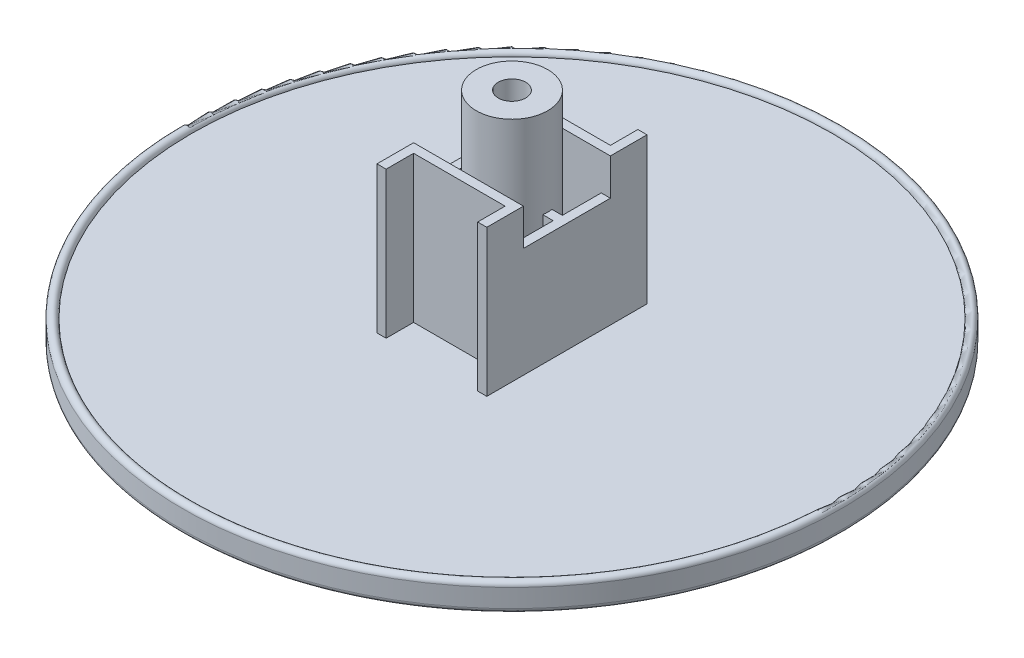
SolidWorks part; units mm, degrees
ref_plane "前视基准面" through (0, 0, 0) normal (0, 0, 1) x (1, 0, 0)
ref_plane "上视基准面" through (0, 0, 0) normal (0, 1, 0) x (1, 0, 0)
ref_plane "右视基准面" through (0, 0, 0) normal (1, 0, 0) x (0, 0, -1)
sketch "草图3" plane through (0, 0, 0) normal (0, 0, 1) x (1, 0, 0)
  line L5 (0, 0) -> (35, 0)
  line L6 (0, 0) -> (0, 2)
  line L11 (0, 2) -> (35, 2)
  line L12 (35, 0) -> (35, 2)
  line L17 (0, 0) -> (35, 2) construction
  line L18 (0, 2) -> (35, 0) construction
  line L19 (35, 0) -> (36, 0)
  line L20 (35, 0) -> (35, 2)
  line L21 (35, 2) -> (36, 2)
  line L22 (36, 0) -> (36, 2)
  line L23 (35, 0) -> (36, 2) construction
  line L24 (35, 2) -> (36, 0) construction
  line L25 (0, 2) -> (3.9, 2)
  line L26 (0, 2) -> (0, 23.6)
  line L27 (0, 23.6) -> (3.9, 23.6)
  line L28 (3.9, 2) -> (3.9, 23.6)
  line L29 (0, 2) -> (3.9, 23.6) construction
  line L30 (0, 23.6) -> (3.9, 2) construction
  line L31 (0, 2) -> (1.5, 2)
  line L32 (0, 2) -> (0, 23.6)
  line L33 (0, 23.6) -> (1.5, 23.6)
  line L34 (1.5, 2) -> (1.5, 23.6)
  line L35 (0, 2) -> (1.5, 23.6) construction
  line L36 (0, 23.6) -> (1.5, 2) construction
  circle A0 centre (35.5, 2) radius 0.5
  circle A1 centre (35.5, 0) radius 0.5
  point P5 (17.5, 1)
  point P9 (35.5, 1)
  point P14 (1.95, 12.8)
  point P19 (0.75, 12.8)
  dimension "D5" = 21.6
  dimension "D1" = 2
  dimension "D2" = 35
  dimension "D3" = 2
  dimension "D4" = 1
  dimension "D6" = 3.9
  dimension "D7" = 21.6
  dimension "D8" = 1.5
revolve "旋转2" add sketch "草图3" angle 360 about L26
sketch "草图4" plane through (0, 2, 0) normal (0, 1, 0) x (1, 0, 0)
  line L0 (-5, -4.75) -> (-6, -4.75)
  line L1 (-5, -4.75) -> (5, -4.75)
  line L2 (-5, -4.75) -> (-5, 4.75)
  line L3 (-5, 4.75) -> (5, 4.75)
  line L4 (5, -4.75) -> (5, 4.75)
  line L5 (0, 4.75) -> (0, -4.75) construction
  line L6 (-5, 0) -> (5, 0) construction
  line L7 (-6, -5.75) -> (6, -5.75)
  line L8 (-6, -5.75) -> (-6, 5.75)
  line L9 (-6, 5.75) -> (6, 5.75)
  line L10 (6, -5.75) -> (6, 5.75)
  line L11 (0, 5.75) -> (0, -5.75) construction
  line L12 (-6, 0) -> (6, 0) construction
  line L13 (-6, -4.75) -> (6, -4.75)
  line L14 (-5, 4.75) -> (-6, 4.75)
  line L15 (-6, 4.75) -> (6, 4.75)
  line L17 (-6, -5.75) -> (-5, -5.75)
  line L18 (-6, -5.75) -> (-6, -8.75)
  line L19 (-6, -8.75) -> (-5, -8.75)
  line L20 (-5, -5.75) -> (-5, -8.75)
  line L21 (-6, -5.75) -> (-5, -8.75) construction
  line L22 (-6, -8.75) -> (-5, -5.75) construction
  line L23 (6, -5.75) -> (5, -5.75)
  line L24 (6, -5.75) -> (6, -8.75)
  line L25 (6, -8.75) -> (5, -8.75)
  line L26 (5, -5.75) -> (5, -8.75)
  line L27 (6, -5.75) -> (5, -8.75) construction
  line L28 (6, -8.75) -> (5, -5.75) construction
  line L29 (-6, 5.75) -> (-5, 5.75)
  line L30 (-6, 5.75) -> (-6, 8.75)
  line L31 (-6, 8.75) -> (-5, 8.75)
  line L32 (-5, 5.75) -> (-5, 8.75)
  line L33 (-6, 5.75) -> (-5, 8.75) construction
  line L34 (-6, 8.75) -> (-5, 5.75) construction
  line L35 (6, 5.75) -> (5, 5.75)
  line L36 (6, 5.75) -> (6, 8.75)
  line L37 (6, 8.75) -> (5, 8.75)
  line L38 (5, 5.75) -> (5, 8.75)
  line L39 (6, 5.75) -> (5, 8.75) construction
  line L40 (6, 8.75) -> (5, 5.75) construction
  point P0 (0, 0)
  point P4 (0, 0)
  point P21 (-5.5, -7.25)
  point P25 (5.5, -7.25)
  point P29 (-5.5, 7.25)
  point P33 (5.5, 7.25)
  dimension "D1" = 9.5
  dimension "D2" = 10
  dimension "D3" = 11.5
  dimension "D4" = 12
  dimension "D5" = 3
  dimension "D6" = 3
  dimension "D7" = 3
  dimension "D8" = 3
extrude "凸台-拉伸1" add sketch "草图4" along normal blind 16 contours L9 L32 L31 L30 | L3 L15 L10 L9 L8 L14 | L38 L9 L36 L37 | L13 L1 L0 L8 L7 L10 | L20 L7 L18 L19 | L7 L26 L25 L24
sketch "草图6" plane through (0, 2, 0) normal (0, 1, 0) x (1, 0, 0)
  line L0 (-3.8298, 0.5) -> (-3.8298, -0.5)
  line L1 (-6, 4.75) -> (-5, 4.75)
  line L2 (-6, 4.75) -> (-6, -4.75)
  line L3 (-6, -4.75) -> (-5, -4.75)
  line L4 (-5, 4.75) -> (-5, -4.75)
  line L5 (-6, 4.75) -> (-5, -4.75) construction
  line L6 (-6, -4.75) -> (-5, 4.75) construction
  line L7 (-6, -4.75) -> (6, -4.75) construction
  line L8 (-0.5, -4.75) -> (0.5, -4.75)
  line L9 (6, 4.75) -> (5, 4.75)
  line L10 (6, 4.75) -> (6, -4.75)
  line L11 (6, -4.75) -> (5, -4.75)
  line L12 (5, 4.75) -> (5, -4.75)
  line L13 (6, 4.75) -> (5, -4.75) construction
  line L14 (6, -4.75) -> (5, 4.75) construction
  line L15 (-0.5, -4.75) -> (-0.5, 4.75)
  line L16 (-0.5, 4.75) -> (0.5, 4.75)
  line L17 (0.5, -4.75) -> (0.5, 4.75)
  line L18 (0, 4.75) -> (0, -4.75) construction
  line L19 (-0.5, 0) -> (0.5, 0) construction
  line L20 (-5, -0.5) -> (5, -0.5)
  line L21 (-5, -0.5) -> (-5, 0.5)
  line L22 (-5, 0.5) -> (5, 0.5)
  line L23 (5, -0.5) -> (5, 0.5)
  line L24 (0, 0.5) -> (0, -0.5) construction
  line L25 (-5, 0) -> (5, 0) construction
  line L26 (-3.8298, -0.5) -> (3.83, -0.5)
  line L27 (3.83, -0.5) -> (3.83, 0.5)
  point P4 (-5.5, 0)
  point P6 (0, 0)
  point P13 (5.5, 0)
  point P18 (0, 0)
  line M17 (6, 4.75) -> (-6, 4.75)
  line M26 (-6, -4.75) -> (6, -4.75)
  circle M34 centre (0, 0) radius 3.9
  dimension "D1" = 9.5
  dimension "D2" = 1
  dimension "D3" = 9.5
  dimension "D4" = 1
  dimension "D5" = 9.5
  dimension "D6" = 1
  dimension "D7" = 1
  dimension "D8" = 10
extrude "凸台-拉伸2" add sketch "草图6" along normal blind 12 contours L4 L2 M17 M26 | L17 L15 M26 M34 | L17 L15 M34 M17 | L22 L4 L20 M34 | L22 L20 L12 M34 | L12 L10 M17 M26
